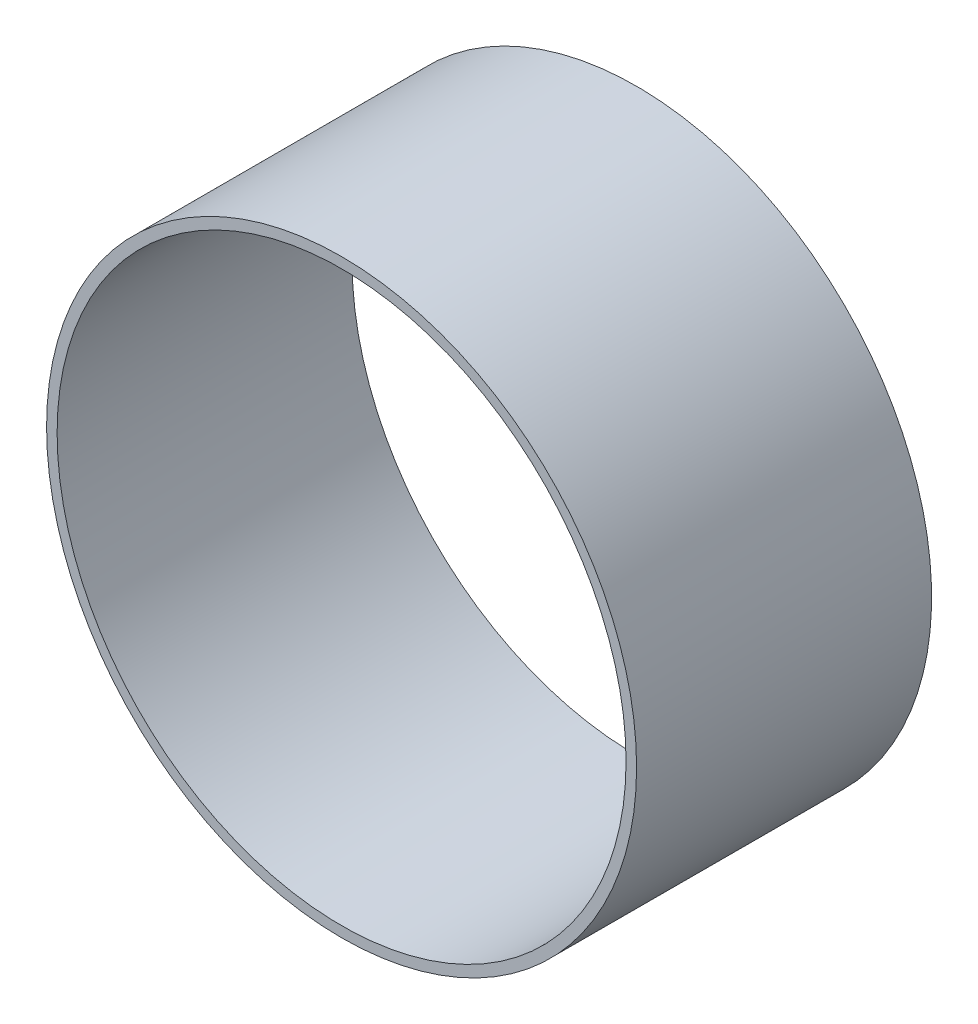
SolidWorks part; units mm, degrees
ref_plane "Front Plane" through (0, 0, 0) normal (0, 0, 1) x (1, 0, 0)
ref_plane "Top Plane" through (0, 0, 0) normal (0, 1, 0) x (1, 0, 0)
ref_plane "Right Plane" through (0, 0, 0) normal (1, 0, 0) x (0, 0, -1)
sketch "Sketch1" plane through (0, 0, 0) normal (0, 0, 1) x (1, 0, 0)
  circle A0 centre (0, 0) radius 14
  circle A1 centre (0, 0) radius 13.5
extrude "Boss-Extrude1" add sketch "Sketch1" along normal blind 19
sketch "Sketch2" plane through (0, 0, 0) normal (0, 0, -1) x (-1, 0, 0)
  circle A0 centre (0, 0) radius 8.2051
  circle A1 centre (0, 0) radius 22.694
extrude "Cut-Extrude1" cut sketch "Sketch2" against normal blind 5
